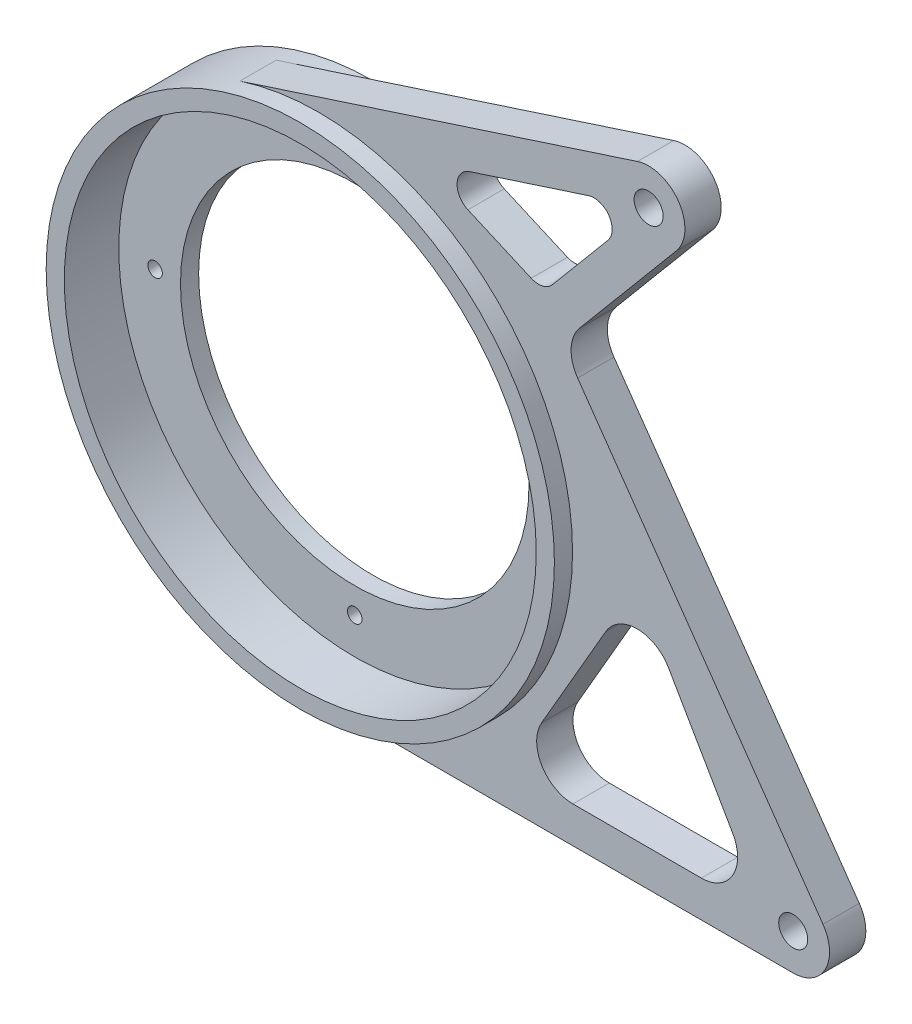
SolidWorks part; units mm, degrees
ref_plane "前视基准面" through (0, 0, 0) normal (0, 0, 1) x (1, 0, 0)
ref_plane "上视基准面" through (0, 0, 0) normal (0, 1, 0) x (1, 0, 0)
ref_plane "右视基准面" through (0, 0, 0) normal (1, 0, 0) x (0, 0, -1)
other "Configuration Table"
sketch "草图1" plane through (0, 0, 0) normal (0, 0, 1) x (1, 0, 0)
  circle A0 centre (0, 0) radius 70
  circle A1 centre (0, 0) radius 48
  circle A2 centre (0, 0) radius 65
  circle A3 centre (0, 0) radius 55 construction
  circle A4 centre (55, 0) radius 2
  circle A5 centre (0, -55) radius 2
  circle A6 centre (-55, 0) radius 2
  circle A7 centre (0, 55) radius 2
  point P88 (0, 0)
  dimension "D1" = 140
  dimension "D2" = 96
  dimension "D3" = 130
  dimension "D4" = 110
  dimension "D5" = 4
  dimension "D6" = 4
extrude "凸台-拉伸3" add sketch "草图1" along normal blind 5
sketch "草图2" plane through (0, 0, 5) normal (0, 0, 1) x (1, 0, 0)
  circle A0 centre (0, 0) radius 70
  circle A1 centre (0, 0) radius 65
  dimension "D1" = 140
  dimension "D2" = 130
extrude "凸台-拉伸4" add sketch "草图2" along normal blind 15
sketch "草图4" plane through (0, 0, 0) normal (0, 0, 1) x (1, 0, 0)
  line L0 (0, -70) -> (130.7902, -70)
  line L1 (-21.6312, 66.574) -> (87.86, 102.1498)
  line L2 (98.6106, 86.2114) -> (71.9311, 54.416)
  line L3 (71.4001, 42.2523) -> (138.9817, -54.2642)
  line L4 (0, 0) -> (160.0247, 0) construction
  line L5 (70.1107, -60) -> (105.4697, -60)
  line L6 (114.1299, -45) -> (96.4504, -14.3782)
  line L7 (79.1299, -14.3782) -> (61.4504, -45)
  line L8 (74.3665, 87.2509) -> (41.6426, 76.6182)
  line L9 (41.1841, 67.2819) -> (58.5963, 59.6667)
  line L10 (64.43, 61.0338) -> (79.7418, 79.2817)
  circle A0 centre (0, 0) radius 70 construction
  circle A1 centre (0, 0) radius 70
  arc A2 (130.7902, -70) -> (138.9817, -54.2642) centre (130.7902, -60) ccw
  arc A3 (71.4001, 42.2523) -> (71.9311, 54.416) centre (79.5916, 47.9881) cw
  arc A4 (98.6106, 86.2114) -> (87.86, 102.1498) centre (90.9502, 92.6392) ccw
  circle A5 centre (90.9502, 92.6392) radius 4
  circle A6 centre (130.7902, -60) radius 4
  circle A7 centre (90.9502, 92.6392) radius 10 construction
  arc A9 (105.4697, -60) -> (114.1299, -45) centre (105.4697, -50) ccw
  arc A10 (70.1107, -60) -> (61.4504, -45) centre (70.1107, -50) cw
  arc A11 (96.4504, -14.3782) -> (79.1299, -14.3782) centre (87.7902, -19.3782) ccw
  arc A12 (64.43, 61.0338) -> (58.5963, 59.6667) centre (60.5998, 64.2477) cw
  arc A13 (41.1841, 67.2819) -> (41.6426, 76.6182) centre (43.1876, 71.8629) cw
  arc A14 (79.7418, 79.2817) -> (74.3665, 87.2509) centre (75.9116, 82.4956) ccw
  point P13 (150, -70)
  point P18 (121.0273, 112.9265)
  point P27 (122.7902, -60)
  point P30 (52.7902, -60)
  point P37 (62.0247, 58.1672)
  point P40 (29.1315, 72.5531)
  dimension "D4" = 10
  dimension "D7" = 8
  dimension "D8" = 8
  dimension "D13" = 10
  dimension "D16" = 5
  dimension "D1" = 18
  dimension "D2" = 150
  dimension "D3" = 150
  dimension "D5" = 55
  dimension "D6" = 50
  dimension "D9" = 60
  dimension "D10" = 60
  dimension "D11" = 70
  dimension "D12" = 8
  dimension "D14" = 65
  dimension "D15" = 45
extrude "凸台-拉伸5" add sketch "草图4" along normal blind 20 contours L2 A4 L1 A1 L0 A2 L3 A3 A14 L10 A12 L9 A13 L8 A11 L6 A9 L5 A10 L7 A6 A5
sketch "草图5" plane through (0, 0, 20) normal (0, 0, 1) x (1, 0, 0)
  line L0 (-21.6312, 66.574) -> (116.7291, 111.5299)
  line L1 (116.7291, 111.5299) -> (175.7117, -70)
  line L2 (175.7117, -70) -> (0, -70)
  arc A0 (0, -70) -> (-21.6312, 66.574) centre (0, 0) ccw
extrude "切除-拉伸1" cut sketch "草图5" against normal blind 5
sketch "草图6" plane through (0, 0, 0) normal (0, 0, -1) x (-1, 0, 0)
  line L0 (0, -70) -> (-171.7448, -70)
  line L1 (-171.7448, -70) -> (-152.5845, 114.8341)
  line L2 (-152.5845, 114.8341) -> (-131.3396, 125.7992)
  line L3 (-131.3396, 125.7992) -> (25.232, 65.2943)
  arc A0 (25.232, 65.2943) -> (0, -70) centre (0, 0) ccw
extrude "切除-拉伸2" cut sketch "草图6" against normal blind 5
